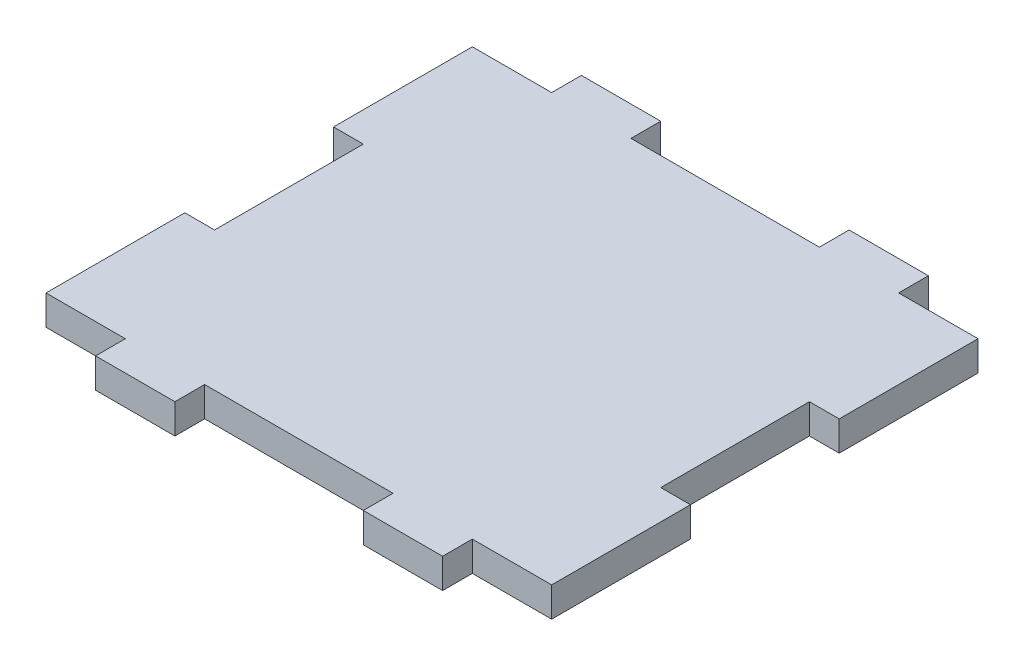
SolidWorks part; units mm, degrees
ref_plane "前视基准面" through (0, 0, 0) normal (0, 0, 1) x (1, 0, 0)
ref_plane "上视基准面" through (0, 0, 0) normal (0, 1, 0) x (1, 0, 0)
ref_plane "右视基准面" through (0, 0, 0) normal (1, 0, 0) x (0, 0, -1)
other "Configuration Table"
sketch "草图1" plane through (0, 0, 0) normal (0, 1, 0) x (1, 0, 0)
  line L0 (0, 10.1458) -> (0, -12.9949) construction
  line L1 (-25.5, 21.5) -> (25.5, 21.5)
  line L2 (-25.5, 21.5) -> (-25.5, -21.5)
  line L3 (-25.5, -21.5) -> (25.5, -21.5)
  line L4 (25.5, 21.5) -> (25.5, -21.5)
  line L5 (-25.5, 21.5) -> (25.5, -21.5) construction
  line L6 (-25.5, -21.5) -> (25.5, 21.5) construction
  line L7 (-17.5, 21.5) -> (-9.5, 21.5)
  line L8 (-17.5, 21.5) -> (-17.5, 24.5)
  line L9 (-17.5, 24.5) -> (-9.5, 24.5)
  line L10 (-9.5, 21.5) -> (-9.5, 24.5)
  line L11 (17.5, 24.5) -> (9.5, 24.5)
  line L12 (9.5, 21.5) -> (9.5, 24.5)
  line L13 (17.5, 21.5) -> (9.5, 21.5)
  line L14 (17.5, 21.5) -> (17.5, 24.5)
  line L15 (-5.5246, 0) -> (5.7331, 0) construction
  line L16 (17.5, -21.5) -> (17.5, -24.5)
  line L17 (17.5, -21.5) -> (9.5, -21.5)
  line L18 (9.5, -21.5) -> (9.5, -24.5)
  line L19 (17.5, -24.5) -> (9.5, -24.5)
  line L20 (-17.5, -24.5) -> (-9.5, -24.5)
  line L21 (-9.5, -21.5) -> (-9.5, -24.5)
  line L22 (-17.5, -21.5) -> (-9.5, -21.5)
  line L23 (-17.5, -21.5) -> (-17.5, -24.5)
  line L24 (25.5, -7.5) -> (22.5, -7.5)
  line L25 (-25.5, 7.5) -> (-22.5, 7.5)
  line L26 (-25.5, 7.5) -> (-25.5, -7.5)
  line L27 (-25.5, -7.5) -> (-22.5, -7.5)
  line L28 (-22.5, 7.5) -> (-22.5, -7.5)
  line L29 (22.5, 7.5) -> (22.5, -7.5)
  line L30 (25.5, 7.5) -> (22.5, 7.5)
  line L31 (25.5, 7.5) -> (25.5, -7.5)
  point P0 (0, 0)
  point P30 (-22.5, 0)
  dimension "D1" = 43
  dimension "D2" = 19
  dimension "D3" = 8
  dimension "D4" = 3
  dimension "D5" = 8
  dimension "D6" = 3
  dimension "D7" = 15
extrude "凸台-拉伸1" add sketch "草图1" along normal blind 3 contours L30 L4 L1 L2 L25 L28 L27 L3 L24 L29 | L1 L10 L9 L8 | L1 L14 L11 L12 | L19 L16 L3 L18 | L3 L23 L20 L21
